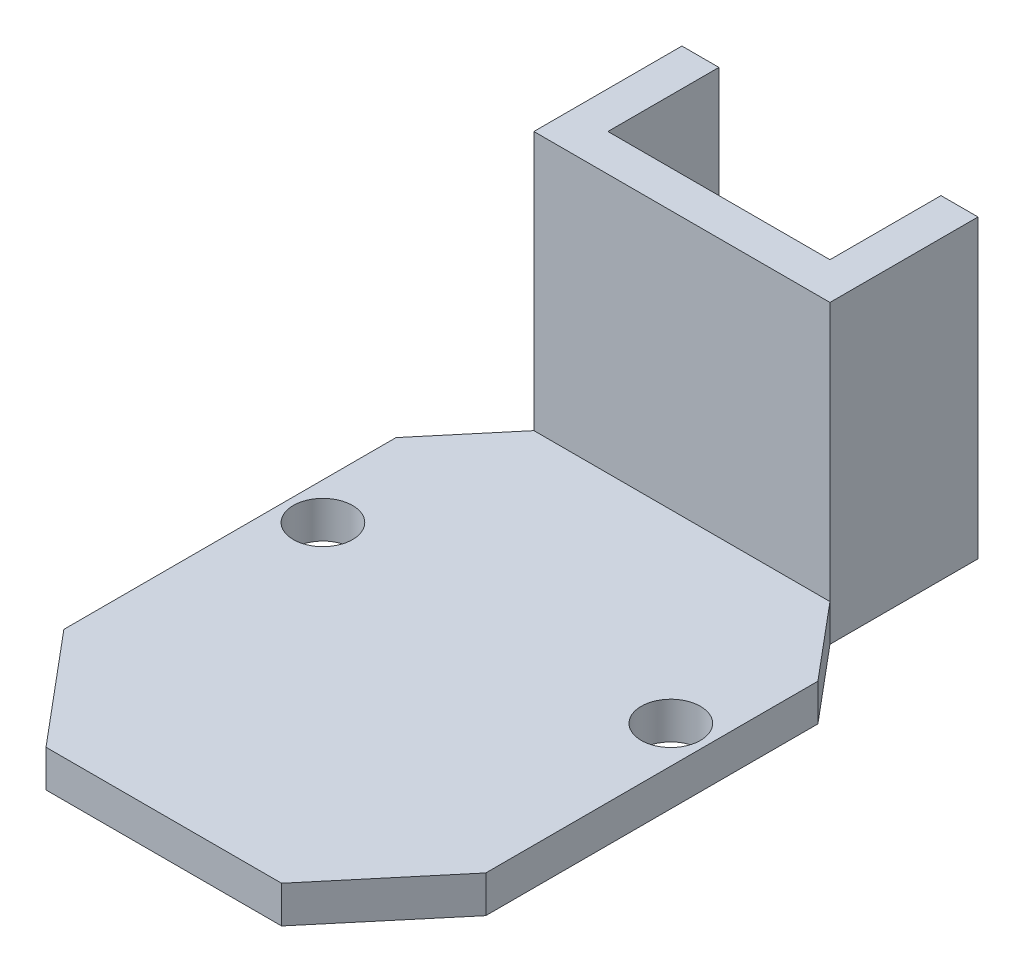
SolidWorks part; units mm, degrees
material "Dökme Alaşımlı Çelik"
ref_plane "Ön Düzlem" through (0, 0, 0) normal (0, 0, 1) x (1, 0, 0)
ref_plane "Üst Düzlem" through (0, 0, 0) normal (0, 1, 0) x (1, 0, 0)
ref_plane "Sağ Düzlem" through (0, 0, 0) normal (1, 0, 0) x (0, 0, -1)
sketch "Sketch1" plane through (0, 0, 0) normal (0, 0, 1) x (1, 0, 0)
  line L0 (0, 0) -> (0, 40)
  line L1 (0, 40) -> (40, 40)
  line L2 (40, 40) -> (40, 0)
  line L3 (0, 0) -> (40, 0)
  dimension "D1" = 40
  dimension "D2" = 40
extrude "Boss-Extrude1" add sketch "Sketch1" along normal blind 20
sketch "Sketch2" plane through (0, 0, 0) normal (0, 0, -1) x (-1, 0, 0)
  line L0 (0, 40) -> (0, 0) construction
  line L1 (-40, 0) -> (-40, 40) construction
  line L2 (0, 40) -> (0, 0)
  line L3 (-40, 0) -> (-40, 40)
  line L4 (-35, 0) -> (-35, 40)
  line L5 (-5, 40) -> (-5, 0)
  line L6 (-35, 40) -> (-5, 40)
  line L7 (-35, 0) -> (-5, 0)
  line M4 (-40, 0) -> (0, 0)
  line M6 (0, 40) -> (-40, 40)
  dimension "D1" = 5
extrude "Cut-Extrude1" cut sketch "Sketch2" against normal blind 15 contours L5 L4 M6 M4
sketch "Sketch3" plane through (0, 0, 20) normal (0, 0, 1) x (1, 0, 0)
  line L0 (-8.5, 0) -> (48.5, 0)
  line L1 (0, 0) -> (40, 0) construction
  line L2 (0, 40) -> (0, 0) construction
  line L3 (-8.5, 0) -> (-8.5, 5)
  line L4 (-8.5, 5) -> (48.5, 5)
  line L5 (48.5, 5) -> (48.5, 0)
  point P2 (20, 0)
  point P5 (20, 0)
  dimension "D1" = 57
  dimension "D2" = 0
  dimension "D3" = 8.5
  dimension "D4" = 5
extrude "Boss-Extrude2" add sketch "Sketch3" along normal blind 70
draft "Draft1" type of draft neutral plane draft angle 50 faces to draft 1 face at (-4.25, 2.5, 20) neutral plane through (0, 0, 20) neutral plane normal (-1, 0, 0) parameters "D1"=50
draft "Draft2" type of draft neutral plane draft angle 50 faces to draft 1 face at (44.25, 2.5, 20) neutral plane through (40, 40, 20) neutral plane normal (1, 0, 0) parameters "D1"=50
chamfer "Chamfer1" distance 15 angle 40 2 edges at (-8.5, 2.5, 90) (48.5, 2.5, 90)
sketch "Sketch6" plane through (0, 5, 0) normal (0, 1, 0) x (1, 0, 0)
  line L0 (-3.5, -20) -> (-3.5, -45) construction
  line L1 (40, -20) -> (0, -20) construction
  line L2 (-3.5, -45) -> (-8.5, -45) construction
  line L3 (-8.5, -75) -> (-8.5, -30.1299) construction
  line L4 (20, -20) -> (20, -54.8323) construction
  circle A0 centre (-3.5, -45) radius 4
  circle A1 centre (43.5, -45) radius 4
  dimension "D3" = 8
  dimension "D1" = 25
  dimension "D2" = 5
extrude "Cut-Extrude3" cut sketch "Sketch6" against normal through all
